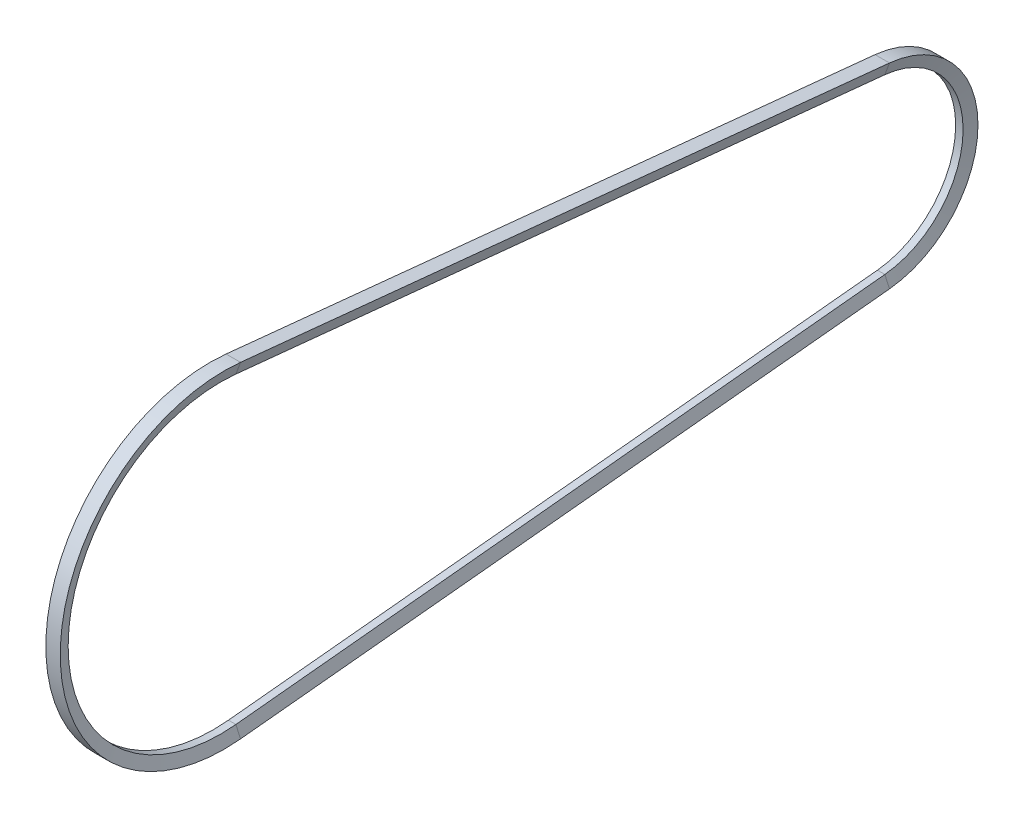
SolidWorks part; units mm, degrees
ref_plane "前视基准面" through (0, 0, 0) normal (0, 0, 1) x (1, 0, 0)
ref_plane "上视基准面" through (0, 0, 0) normal (0, 1, 0) x (1, 0, 0)
ref_plane "右视基准面" through (0, 0, 0) normal (1, 0, 0) x (0, 0, -1)
sketch "草图1" plane through (0, 0, 0) normal (1, 0, 0) x (0, 0, -1)
  line L0 (12.5, 124.3734) -> (507.5, 74.6241)
  line L1 (12.5, -124.3734) -> (507.5, -74.6241)
  line L2 (0, 0) -> (500, 0) construction
  arc A0 (12.5, 124.3734) -> (12.5, -124.3734) centre (0, 0) ccw
  arc A1 (507.5, -74.6241) -> (507.5, 74.6241) centre (500, 0) ccw
  dimension "D1" = 125
  dimension "D2" = 75
  dimension "D3" = 500
sketch "草图2" plane through (0, 0, 0) normal (0, 0, 1) x (1, 0, 0)
  line L0 (-5.5, 125) -> (5.5, 125)
  line L1 (5.5, 125) -> (2.8401, 116.3)
  line L2 (2.8401, 116.3) -> (-2.8401, 116.3)
  line L3 (-2.8401, 116.3) -> (-5.5, 125)
  line L4 (0, 116.3) -> (0, 125) construction
  line L5 (0, -125) -> (0, 125) construction
  dimension "D1" = 11
  dimension "D2" = 8.7
  dimension "D3" = 34
sweep "扫描1" add profiles "草图2" path "草图1"
equation "\"D3@草图1\" = \"D1@距离1@椭圆辐轮_椭圆辐轮.Assembly\""
equation "\"D1@草图2\" = \"bd@草图1@大带轮_椭圆辐轮.Part\" "
equation "\"D2@草图2\" = \"hf@草图1@大带轮_椭圆辐轮.Part\" "
equation "\"D3@草图2\" = \"槽轮角@草图1@大带轮_椭圆辐轮.Part\" "
equation "\"D2@草图1\" = \"dd@草图1@小带轮_椭圆辐轮.Part\"/2  "
equation "\"D1@草图1\" = \"dd@草图1@大带轮_椭圆辐轮.Part\" /2"
